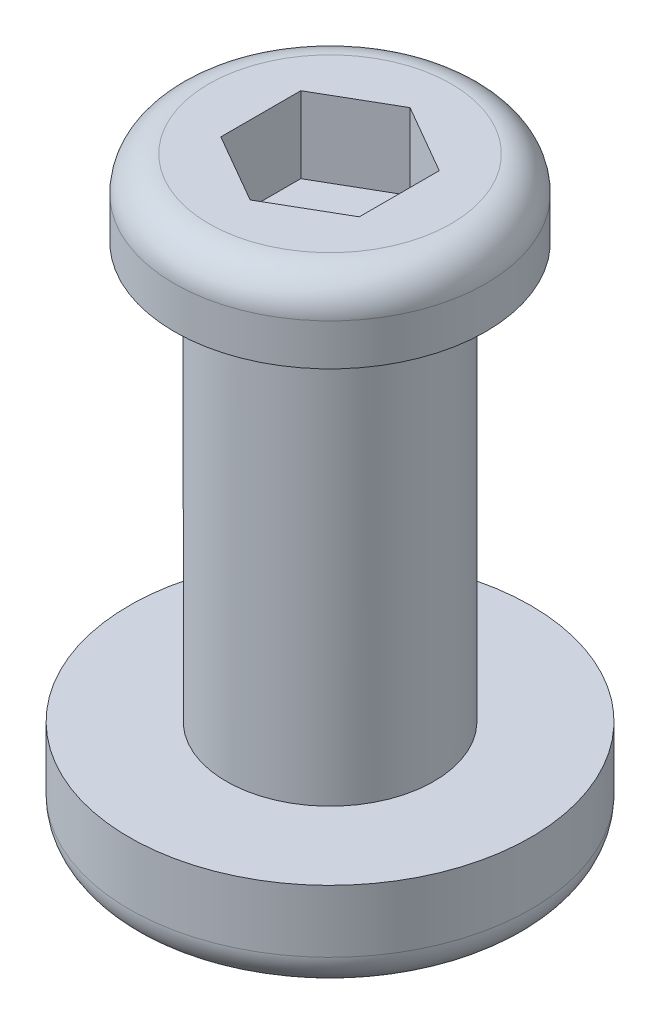
SolidWorks part; units mm, degrees
material "AISI 304"
ref_plane "前视基准面" through (0, 0, 0) normal (0, 0, 1) x (1, 0, 0)
ref_plane "上视基准面" through (0, 0, 0) normal (0, 1, 0) x (1, 0, 0)
ref_plane "右视基准面" through (0, 0, 0) normal (1, 0, 0) x (0, 0, -1)
other "Configuration Table"
sketch "草图1" plane through (0, 0, 0) normal (0, 1, 0) x (1, 0, 0)
  circle A0 centre (0, 0) radius 1.5
  dimension "D1" = 3
extrude "凸台-拉伸1" add sketch "草图1" along normal blind 6
sketch "草图2" plane through (0, 6, 0) normal (0, 1, 0) x (1, 0, 0)
  line L0 (0, 0) -> (0, 1.8449) construction
  line L1 (0, 1.1547) -> (-1, 0.5774)
  line L2 (-1, 0.5774) -> (-1, -0.5774)
  line L3 (-1, -0.5774) -> (0, -1.1547)
  line L4 (0, -1.1547) -> (1, -0.5774)
  line L5 (1, -0.5774) -> (1, 0.5774)
  line L6 (1, 0.5774) -> (0, 1.1547)
  circle A0 centre (0, 0) radius 2.25
  circle A1 centre (0, 0) radius 1 construction
  dimension "D2" = 4.5
  dimension "D1" = 2
extrude "凸台-拉伸2" add sketch "草图2" along normal blind 1.1
sketch "草图3" plane through (0, 0, 0) normal (0, -1, 0) x (1, 0, 0)
  line L0 (0, 0) -> (0, 3.3681) construction
  line L1 (0, 1.1547) -> (-1, 0.5774)
  line L2 (-1, 0.5774) -> (-1, -0.5774)
  line L3 (-1, -0.5774) -> (0, -1.1547)
  line L4 (0, -1.1547) -> (1, -0.5774)
  line L5 (1, -0.5774) -> (1, 0.5774)
  line L6 (1, 0.5774) -> (0, 1.1547)
  circle A0 centre (0, 0) radius 2.9
  circle A1 centre (0, 0) radius 1 construction
  dimension "D2" = 5.8
  dimension "D1" = 2
extrude "凸台-拉伸3" add sketch "草图3" along normal blind 1.4
fillet "圆角1" radius 0.5 2 edges at (0, 7.1, 2.25) (0, -1.4, -2.9)
